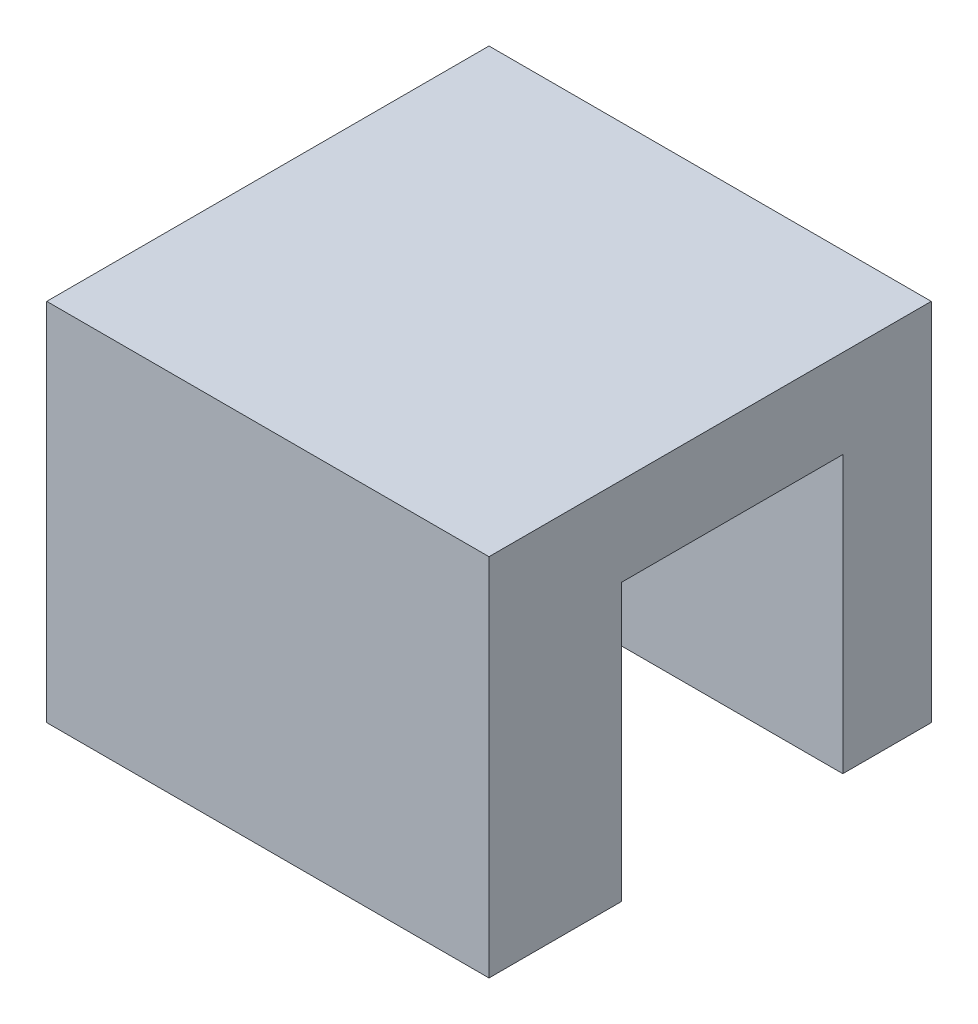
SolidWorks part; units mm, degrees
ref_plane "Front Plane" through (0, 0, 0) normal (0, 0, 1) x (1, 0, 0)
ref_plane "Top Plane" through (0, 0, 0) normal (0, 1, 0) x (1, 0, 0)
ref_plane "Right Plane" through (0, 0, 0) normal (1, 0, 0) x (0, 0, -1)
sketch "Sketch1" plane through (0, 0, 0) normal (0, 1, 0) x (1, 0, 0)
  line L0 (-2.5645, 3.2952) -> (14.4355, 3.2952)
  line L1 (-5.5645, 3.2952) -> (-4.0645, 3.2952)
  line L2 (-5.5645, 3.2952) -> (-5.5645, -2.7048)
  line L3 (-5.5645, -2.7048) -> (14.4355, -2.7048)
  line L4 (14.4355, 3.2952) -> (14.4355, -2.7048)
  line L9 (-2.5645, 3.2952) -> (-4.0645, 3.2952)
  point P5 (0, 0)
  dimension "D1" = 6
  dimension "D3" = 20
extrude "Boss-Extrude1" add sketch "Sketch1" along normal blind 12.5
sketch "Sketch2" plane through (14.4355, 0, 0) normal (1, 0, 0) x (0, 0, -1)
  line L0 (3.2952, 12.5) -> (3.2952, 0) construction
  line L1 (-2.7048, 12.5) -> (13.2952, 12.5)
  line L2 (-2.7048, 12.5) -> (-2.7048, 16.5)
  line L3 (-2.7048, 16.5) -> (17.2952, 16.5)
  line L4 (17.2952, 12.5) -> (17.2952, 16.5)
  line L6 (17.2952, 12.5) -> (17.2952, 0)
  line L7 (17.2952, 0) -> (13.2952, 0)
  line L8 (13.2952, 12.5) -> (13.2952, 0)
  line L10 (-2.7048, 0) -> (3.2952, 0) construction
  dimension "D1" = 4
  dimension "D2" = 4
  dimension "D3" = 10
extrude "Boss-Extrude4" add sketch "Sketch2" against normal blind 20
sketch "Sketch5" plane through (-5.5645, 0, 0) normal (-1, 0, 0) x (0, 0, 1)
  line L0 (-3.2952, 0) -> (2.7048, 0)
  line L1 (-3.2952, 12.5) -> (-3.2952, 0) construction
  line L2 (2.7048, 0) -> (2.7048, 16.5)
  line L3 (2.7048, 16.5) -> (-3.2952, 16.5)
  line L4 (-17.2952, 16.5) -> (2.7048, 16.5) construction
  line L5 (-3.2952, 16.5) -> (-3.2952, 9.5452)
  line L6 (-3.2952, 9.5452) -> (0, 6.25)
  line L7 (0, 6.25) -> (-3.2952, 2.9548)
  line L8 (-3.2952, 2.9548) -> (-3.2952, 0)
  line L9 (-13.2952, 12.5) -> (-13.2952, 0) construction
  line L10 (-13.2952, 0) -> (-3.2952, 12.5) construction
  point P18 (-13.2952, 6.25)
  dimension "D1" = 90
sketch "Sketch3" plane through (0, 0, -17.2952) normal (0, 0, -1) x (-1, 0, 0)
  line L0 (-2.4355, 0) -> (-2.4355, 12.5) construction
  line L1 (-2.4355, 0) -> (-14.4355, 0) construction
  point P0 (-8.4355, 6.25)
  point P3 (-2.4355, 6.25)
  point P6 (-8.4355, 0)
hole_wizard "M2x0.4 Tapped Hole1" positions "3DSketch1" profile "Sketch4" tap size "M2x0.4" standard "BSI"
sketch3d "3DSketch1"
  point P0 (8.4355, 6.25, -17.2952)
sketch "Sketch4" plane through (8.4355, 6.25, -17.2952) normal (1, 0, 0) x (0, 1, 0)
  line L0 (0, 0) -> (0, 4)
  line L1 (0, 4) -> (0.8, 4)
  line L2 (0.8, 4) -> (0.8, 0)
  line L5 (0.8, 0) -> (0, 0)
  line L11 (0, -6.35) -> (0, 107.95) construction
  dimension "Thru Tap Drill Dia." = 1.6
  dimension "Thru Tap Drill Depth" = 4
cosmetic thread "Hole Thread1" parameters "D2"=2
